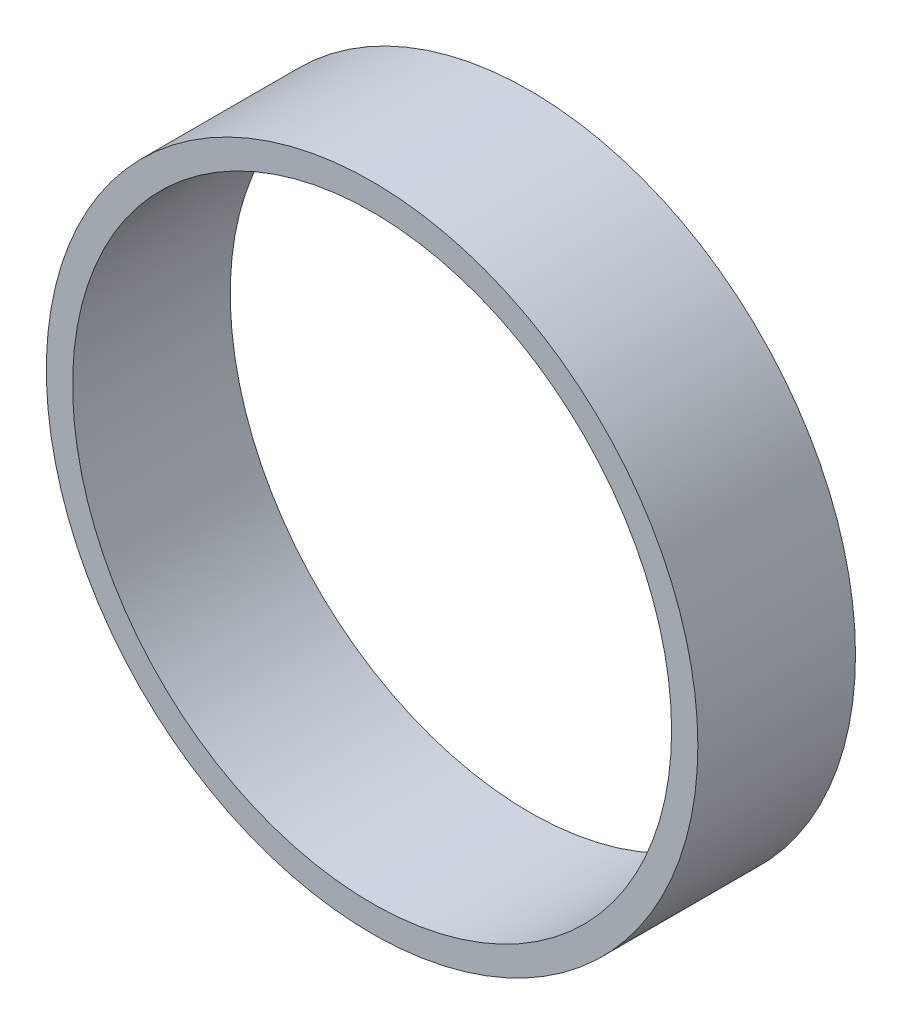
SolidWorks part; units mm, degrees
ref_plane "Front Plane" through (0, 0, 0) normal (0, 0, 1) x (1, 0, 0)
ref_plane "Top Plane" through (0, 0, 0) normal (0, 1, 0) x (1, 0, 0)
ref_plane "Right Plane" through (0, 0, 0) normal (1, 0, 0) x (0, 0, -1)
sketch "Sketch1" plane through (0, 0, 0) normal (0, 0, 1) x (1, 0, 0)
  circle A0 centre (0, 0) radius 31
  circle A1 centre (0, 0) radius 28.5
  dimension "D1" = 62
  dimension "D2" = 57
extrude "Boss-Extrude1" add sketch "Sketch1" along normal blind 15
